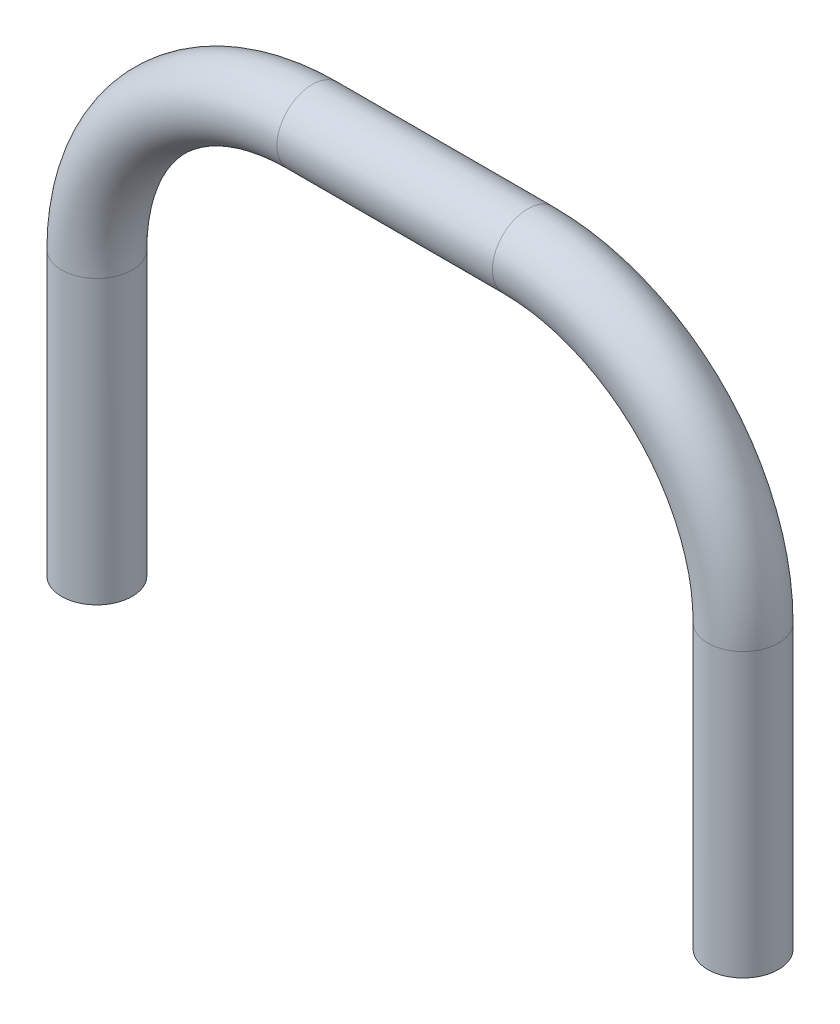
SolidWorks part; units mm, degrees
ref_plane "Front Plane" through (0, 0, 0) normal (0, 0, 1) x (1, 0, 0)
ref_plane "Top Plane" through (0, 0, 0) normal (0, 1, 0) x (1, 0, 0)
ref_plane "Right Plane" through (0, 0, 0) normal (1, 0, 0) x (0, 0, -1)
sketch "Sketch1" plane through (0, 0, 0) normal (0, 0, 1) x (1, 0, 0)
  line L0 (0, 0) -> (0, 266.7)
  line L1 (203.2, 469.9) -> (406.4, 469.9)
  line L2 (609.6, 266.7) -> (609.6, 0)
  arc A0 (203.2, 469.9) -> (0, 266.7) centre (203.2, 266.7) ccw
  arc A1 (406.4, 469.9) -> (609.6, 266.7) centre (406.4, 266.7) cw
  point P7 (0, 469.9)
  point P10 (609.6, 469.9)
  dimension "D4" = 203.2
  dimension "D1" = 609.6
  dimension "D2" = 266.7
  dimension "D3" = 266.7
  dimension "D5" = 266.7
sketch "Sketch2" plane through (0, 0, 0) normal (0, 1, 0) x (1, 0, 0)
  circle A0 centre (0, 0) radius 33.3375
  dimension "D1" = 66.675
sweep "Sweep1" add profiles "Sketch2" path "Sketch1"
sketch "Sketch3" plane through (0, 0, 0) normal (0, -1, 0) x (1, 0, 0)
  circle A0 centre (0, 0) radius 23.8125
  circle A1 centre (0, 0) radius 33.3375 construction
  dimension "D1" = 9.525
extrude "Cut-Extrude1" cut sketch "Sketch3" against normal blind 256.54
sketch "Sketch4" plane through (0, 0, 0) normal (0, -1, 0) x (1, 0, 0)
  circle A0 centre (609.6, 0) radius 23.8125
  circle A1 centre (609.6, 0) radius 33.3375 construction
  dimension "D1" = 9.525
extrude "Cut-Extrude2" cut sketch "Sketch4" against normal blind 261.62
sketch "Sketch5" plane through (0, 0, 0) normal (0, -1, 0) x (1, 0, 0)
  circle A0 centre (0, 0) radius 33.3375 construction
  circle A1 centre (0, 0) radius 33.3375
